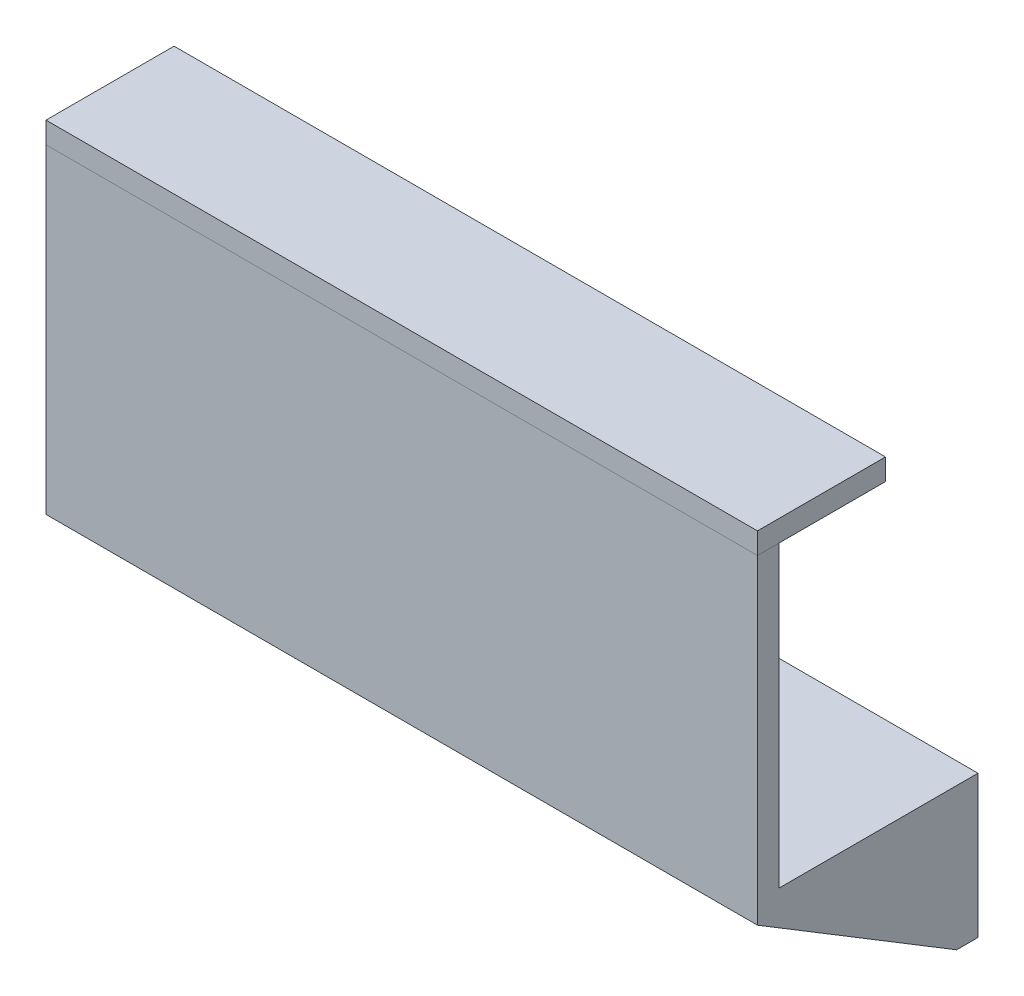
SolidWorks part; units mm, degrees
ref_plane "前视基准面" through (0, 0, 0) normal (0, 0, 1) x (1, 0, 0)
ref_plane "上视基准面" through (0, 0, 0) normal (0, 1, 0) x (1, 0, 0)
ref_plane "右视基准面" through (0, 0, 0) normal (1, 0, 0) x (0, 0, -1)
sketch "草图1" plane through (0, 0, 0) normal (0, 0, 1) x (1, 0, 0)
  line L1 (0, 0) -> (100, 0)
  line L2 (0, 0) -> (0, -20)
  line L3 (0, -20) -> (100, -20)
  line L4 (100, 0) -> (100, -20)
  dimension "D1" = 100
  dimension "D2" = 20
extrude "凸台-拉伸1" add sketch "草图1" along normal blind 3
sketch "草图2" plane through (0, 0, 3) normal (0, 0, 1) x (1, 0, 0)
  line L0 (100, -20) -> (100, 0) construction
  line L1 (0, 0) -> (100, 0)
  line L2 (0, 0) -> (0, -3)
  line L3 (0, -3) -> (100, -3)
  line L4 (100, 0) -> (100, -3)
  dimension "D1" = 3
extrude "凸台-拉伸2" add sketch "草图2" along normal blind 25
sketch "草图3" plane through (0, 0, 28) normal (0, 0, 1) x (1, 0, 0)
  line L0 (0, -3) -> (0, -20) construction
  line L1 (100, -3) -> (0, -3)
  line L2 (100, -3) -> (100, 42)
  line L3 (100, 42) -> (0, 42)
  line L4 (0, -3) -> (0, 42)
  dimension "D1" = 45
extrude "凸台-拉伸3" add sketch "草图3" along normal blind 3
sketch "草图4" plane through (0, 0, 28) normal (0, 0, -1) x (-1, 0, 0)
  line L0 (0, 42) -> (0, 0) construction
  line L1 (-100, 42) -> (0, 42)
  line L2 (-100, 42) -> (-100, 45)
  line L3 (-100, 45) -> (0, 45)
  line L4 (0, 42) -> (0, 45)
  dimension "D1" = 3
extrude "凸台-拉伸4" add sketch "草图4" along normal blind 15 and the other way blind 3 separate body
sketch "草图5" plane through (0, 0, 3) normal (0, 0, 1) x (1, 0, 0)
  line L0 (0, -3) -> (0, -20) construction
  circle A0 centre (10, -6) radius 1.5
  circle A1 centre (89, -6) radius 1.5
  dimension "D1" = 3
  dimension "D3" = 3
  dimension "D2" = 6
  dimension "D4" = 79
  dimension "D5" = 10
extrude "切除-拉伸1" cut sketch "草图5" against normal blind 15
chamfer "倒角1" distance 0.5 angle 45 2 edges at (90.5, -6, 3) (11.5, -6, 3)
sketch "草图6" plane through (0, 0, 0) normal (-1, 0, 0) x (0, 0, 1)
  line L0 (3, -20) -> (31, -3)
  line L1 (31, -3) -> (3, -3)
  line L2 (3, -3) -> (3, -20)
extrude "凸台-拉伸5" add sketch "草图6" against normal blind 2 separate body
sketch "草图7" plane through (100, 0, 0) normal (1, 0, 0) x (0, 0, -1)
  line L3 (-3, -20) -> (-3, -3)
  line L4 (-3, -3) -> (-31, -3)
  line L5 (-31, -3) -> (-3, -20)
  line L6 (-3, -20) -> (-3, -3)
  line L7 (-3, -3) -> (-31, -3)
  line L8 (-31, -3) -> (-3, -20)
  dimension "D1" = 0
extrude "凸台-拉伸6" add sketch "草图7" against normal blind 2
